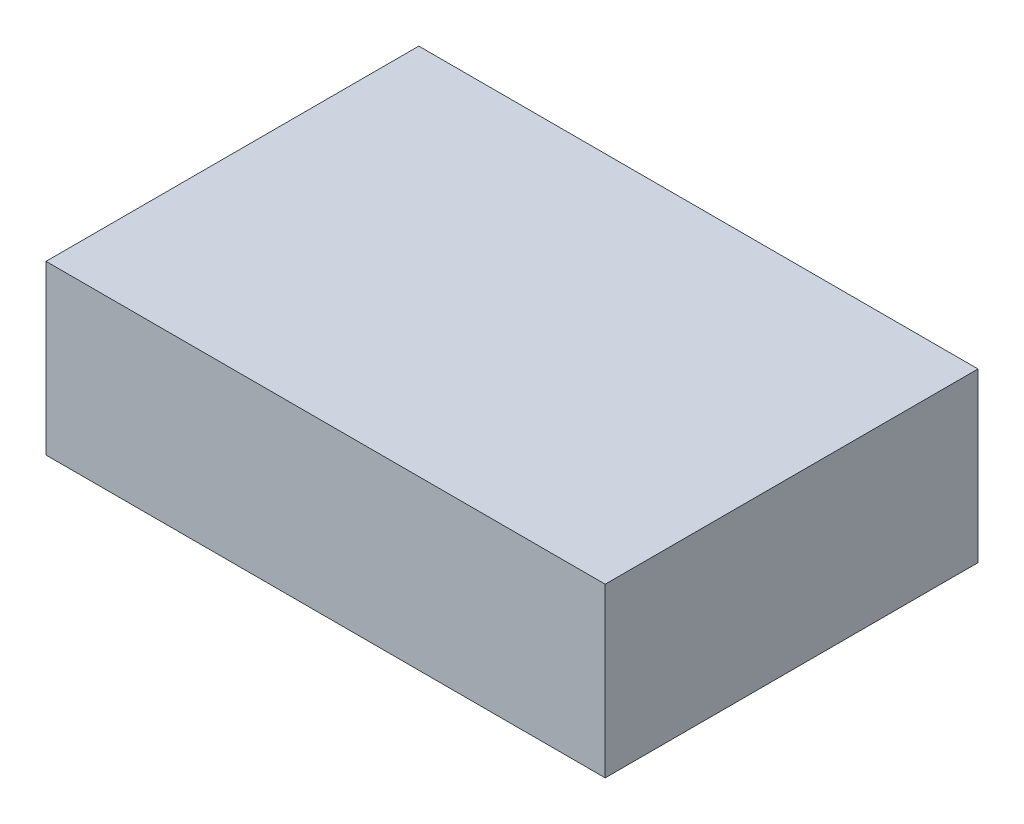
SolidWorks part; units mm, degrees
ref_plane "Front Plane" through (0, 0, 0) normal (0, 0, 1) x (1, 0, 0)
ref_plane "Top Plane" through (0, 0, 0) normal (0, 1, 0) x (1, 0, 0)
ref_plane "Right Plane" through (0, 0, 0) normal (1, 0, 0) x (0, 0, -1)
sketch "Sketch2" plane through (0, 0, 0) normal (0, 1, 0) x (1, 0, 0)
  line L1 (-15, -10) -> (15, -10)
  line L2 (-15, -10) -> (-15, 10)
  line L3 (-15, 10) -> (15, 10)
  line L4 (15, -10) -> (15, 10)
  line L5 (-15, -10) -> (15, 10) construction
  line L6 (-15, 10) -> (15, -10) construction
  point P0 (0, 0)
  dimension "D1" = 30
  dimension "D2" = 20
extrude "Boss-Extrude1" add sketch "Sketch2" along normal blind 9
